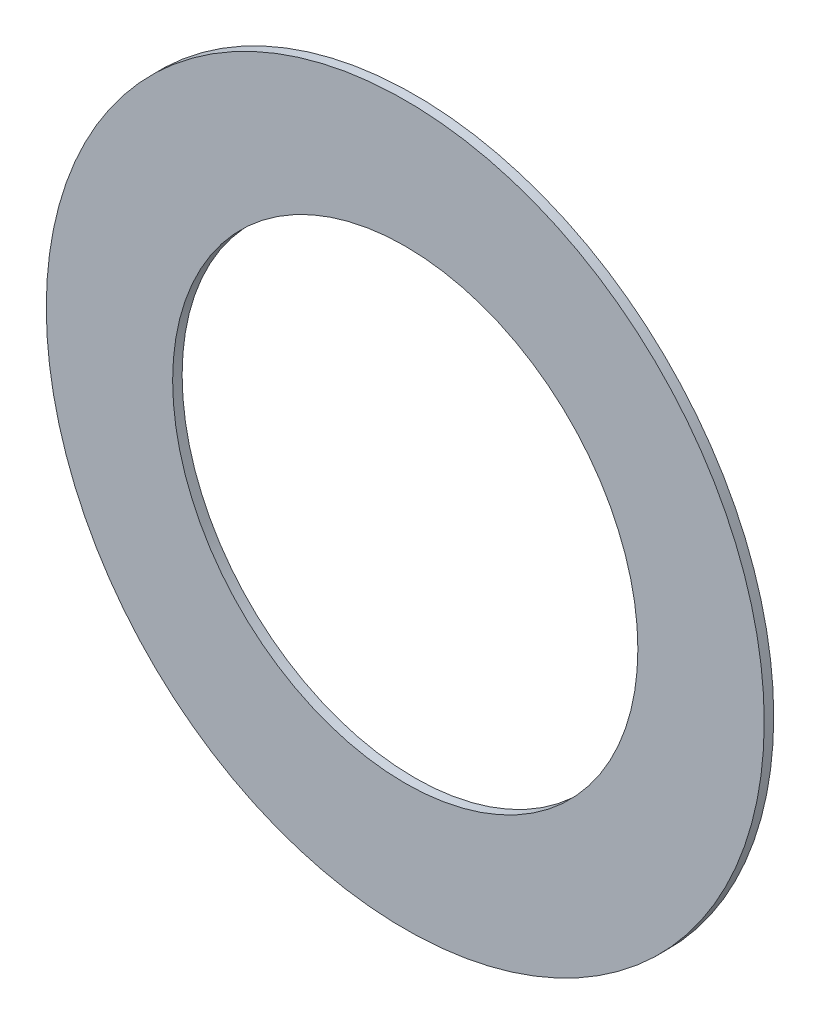
SolidWorks part; units mm, degrees
material "ABS"
ref_plane "Front" through (0, 0, 0) normal (0, 0, 1) x (1, 0, 0)
ref_plane "Top" through (0, 0, 0) normal (0, 1, 0) x (1, 0, 0)
ref_plane "Right" through (0, 0, 0) normal (1, 0, 0) x (0, 0, -1)
sketch "Sketch1" plane through (0, 0, 0) normal (0, 0, 1) x (1, 0, 0)
  circle A0 centre (0, 0) radius 5.1435
  circle A1 centre (0, 0) radius 7.9375
  dimension "D1" = 10.287
  dimension "D2" = 15.875
extrude "Boss-Extrude1" add sketch "Sketch1" along normal blind 0.21
